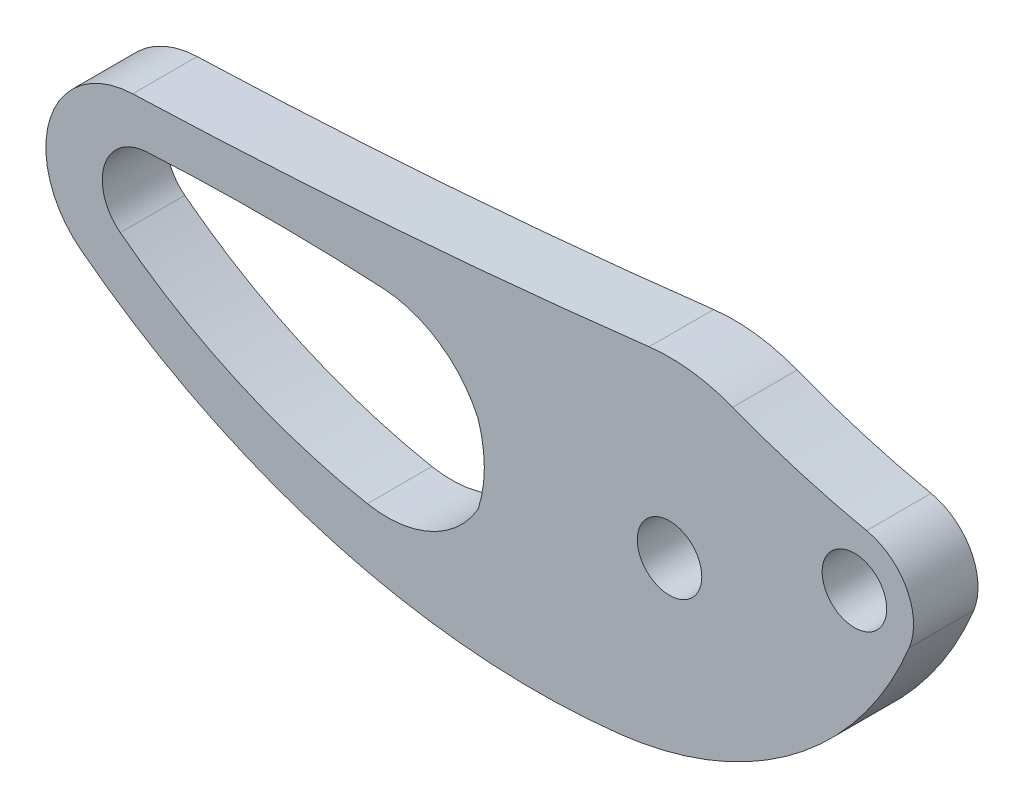
SolidWorks part; units mm, degrees
ref_plane "Plan de face" through (0, 0, 0) normal (0, 0, 1) x (1, 0, 0)
ref_plane "Plan de dessus" through (0, 0, 0) normal (0, 1, 0) x (1, 0, 0)
ref_plane "Plan de droite" through (0, 0, 0) normal (1, 0, 0) x (0, 0, -1)
sketch "Esquisse1" plane through (0, 0, 0) normal (0, 0, 1) x (1, 0, 0)
  line L0 (27.2912, 385.8731) -> (108.8135, 327.9584) construction
  circle A0 centre (0, 0) radius 1.5
  circle A1 centre (8.6, 3) radius 1.5
  arc A2 (-27.3803, -1.2744) -> (-2.3391, -8.2473) centre (-6.2298, 26.2306) ccw
  arc A3 (-2.3391, -8.2473) -> (11.1472, 1.961) centre (-4.1974, 8.2202) ccw
  arc A4 (11.1472, 1.961) -> (9.1663, 5.692) centre (8.6, 3) ccw
  arc A5 (9.1663, 5.692) -> (2.9362, 7.5459) centre (17.3477, 44.5824) cw
  arc A6 (2.9362, 7.5459) -> (-0.9495, 8.0411) centre (0, 0) ccw
  arc A7 (-0.9495, 8.0411) -> (-24.974, 6.2175) centre (-34.7772, 294.5294) cw
  arc A8 (-24.974, 6.2175) -> (-27.3803, -1.2744) centre (-24.832, 2.0395) ccw
  arc A9 (-25.5492, 0.3384) -> (-14.0561, -4.8357) centre (-8.9617, 21.8324) ccw
  arc A10 (-14.0561, -4.8357) -> (-8.9046, -2.48) centre (-13.1384, -0.032) ccw
  arc A11 (-8.9046, -2.48) -> (-8.9046, 1.1655) centre (-14.5098, -0.6572) ccw
  arc A12 (-8.9046, 1.1655) -> (-13.3346, 4.2057) centre (-13.6145, -0.9498) ccw
  arc A13 (-25.5492, 0.3384) -> (-24.3494, 4.2016) centre (-24.2307, 2.0468) cw
  arc A14 (-24.3494, 4.2016) -> (-13.3346, 4.2057) centre (-18.8043, -96.5244) cw
  dimension "D2" = 3
  dimension "D1" = 100
  dimension "D3" = 3
  dimension "D4" = 8.6
extrude "Boss.-Extru.1" add sketch "Esquisse1" along normal blind 3
